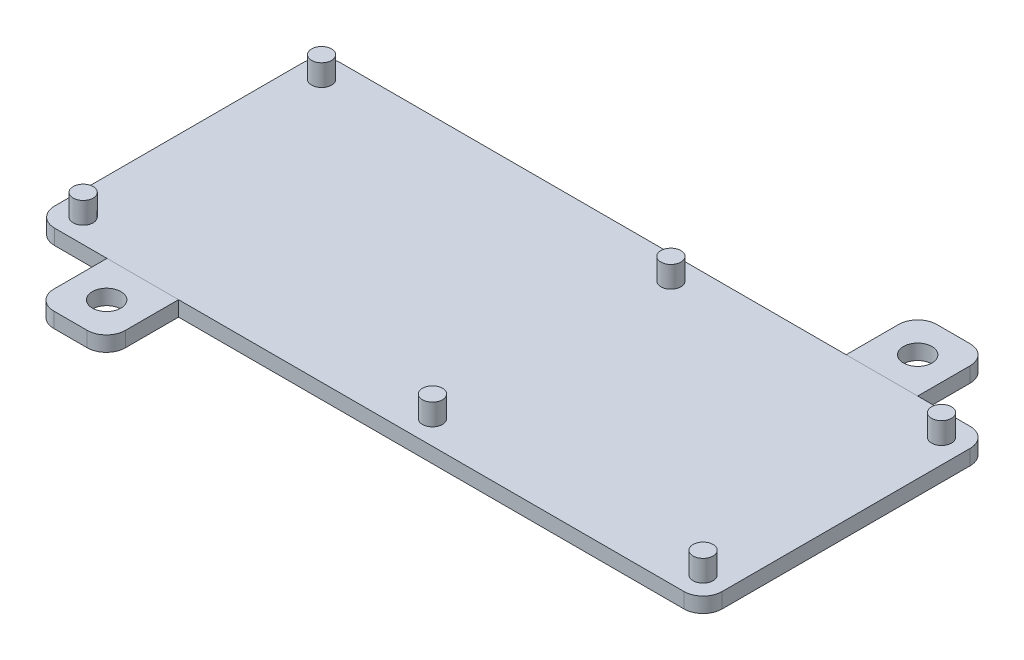
SolidWorks part; units mm, degrees
material "Custom Plastic"
ref_plane "X-Y Datum" through (0, 0, 0) normal (0, 0, 1) x (1, 0, 0)
ref_plane "X-Z Datum" through (0, 0, 0) normal (0, 1, 0) x (1, 0, 0)
ref_plane "Y-Z Datum" through (0, 0, 0) normal (1, 0, 0) x (0, 0, -1)
sketch "Sketch1" plane through (0, -38.0633, 0) normal (0, -1, 0) x (1, 0, 0)
  circle A0 centre (-181.8399, -5.7269) radius 2.0955 construction
  circle A1 centre (-108.5899, -5.7269) radius 2.0955 construction
  circle A2 centre (-51.8399, -5.7269) radius 2.0955 construction
  circle A3 centre (-51.8399, 44.2731) radius 2.0955 construction
  circle A4 centre (-108.5899, 44.2731) radius 2.0955 construction
  circle A5 centre (-181.8399, 44.2731) radius 2.0955 construction
  circle A6 centre (-181.8399, -5.7269) radius 2.0955
  circle A7 centre (-108.5899, -5.7269) radius 2.0955
  circle A8 centre (-51.8399, -5.7269) radius 2.0955
  circle A9 centre (-51.8399, 44.2731) radius 2.0955
  circle A10 centre (-108.5899, 44.2731) radius 2.0955
  circle A11 centre (-181.8399, 44.2731) radius 2.0955
extrude "Boss-Extrude1" add sketch "Sketch1" along normal blind 4.5
sketch "Sketch2" plane through (0, -42.5633, 0) normal (0, -1, 0) x (1, 0, 0)
  line L0 (-186.8399, 19.2731) -> (-46.8399, 19.2731) construction
  line L1 (-186.8399, -10.7269) -> (-186.8399, 49.2731) construction
  line L2 (-46.8399, -10.7269) -> (-46.8399, 49.2731) construction
  line L3 (-116.8399, 49.2731) -> (-116.8399, -10.7269) construction
  line L4 (-186.8399, 49.2731) -> (-46.8399, 49.2731) construction
  line L5 (-186.8399, -10.7269) -> (-46.8399, -10.7269) construction
  line L7 (-186.8399, -10.7269) -> (-46.8399, -10.7269)
  line L8 (-186.8399, -10.7269) -> (-186.8399, 49.2731)
  line L9 (-186.8399, 49.2731) -> (-46.8399, 49.2731)
  line L10 (-46.8399, -10.7269) -> (-46.8399, 49.2731)
  line L11 (-186.8399, -10.7269) -> (-46.8399, 49.2731) construction
  line L12 (-186.8399, 49.2731) -> (-46.8399, -10.7269) construction
  point P12 (-116.8399, 19.2731)
extrude "Boss-Extrude2" add sketch "Sketch2" along normal blind 3.175
fillet "Fillet1" radius 4 4 edges at (-46.8399, -44.1508, -10.7269) (-46.8399, -44.1508, 49.2731) (-186.8399, -44.1508, -10.7269) (-186.8399, -44.1508, 49.2731)
sketch "Sketch3" plane through (0, -45.7383, 0) normal (0, -1, 0) x (1, 0, 0)
  line L0 (-50.8399, 49.2731) -> (-182.8399, 49.2731) construction
  line L1 (-171.8399, 49.2731) -> (-156.8399, 49.2731)
  line L2 (-171.8399, 49.2731) -> (-171.8399, 64.4172)
  line L3 (-171.8399, 64.4172) -> (-156.8399, 64.4172)
  line L4 (-156.8399, 49.2731) -> (-156.8399, 64.4172)
  line L5 (-186.8399, 45.2731) -> (-186.8399, -6.7269) construction
  line L12 (-50.8399, 49.2731) -> (-182.8399, 49.2731) construction
  line L14 (-182.8399, -10.7269) -> (-50.8399, -10.7269) construction
  line L15 (-61.8399, -10.7269) -> (-76.8399, -10.7269)
  line L16 (-61.8399, -10.7269) -> (-61.8399, -25.7269)
  line L17 (-61.8399, -25.7269) -> (-76.8399, -25.7269)
  line L18 (-76.8399, -10.7269) -> (-76.8399, -25.7269)
  line L19 (-46.8399, -10.7269) -> (-46.8399, 49.2731) construction
  line L20 (-171.8399, 56.8452) -> (-156.8399, 56.8452) construction
  line L21 (-164.3399, 49.2731) -> (-164.3399, 64.4172) construction
  line L22 (-76.8399, -18.2269) -> (-61.8399, -18.2269) construction
  line L23 (-69.3399, -25.7269) -> (-69.3399, -10.7269) construction
  circle A0 centre (-164.3399, 56.8452) radius 3
  circle A1 centre (-69.3399, -18.2269) radius 3
  dimension "D7" = 6
  dimension "D8" = 6
  dimension "D1" = 15
  dimension "D2" = 15
  dimension "D3" = 15
  dimension "D4" = 15
  dimension "D5" = 15.1441
  dimension "D6" = 15
extrude "Boss-Extrude3" add sketch "Sketch3" against normal blind 3.175 separate body
fillet "Fillet2" radius 4 2 edges at (-156.8399, -44.1508, 64.4172) (-171.8399, -44.1508, 64.4172)
fillet "Fillet3" radius 4 2 edges at (-76.8399, -44.1508, -25.7269) (-61.8399, -44.1508, -25.7269)
